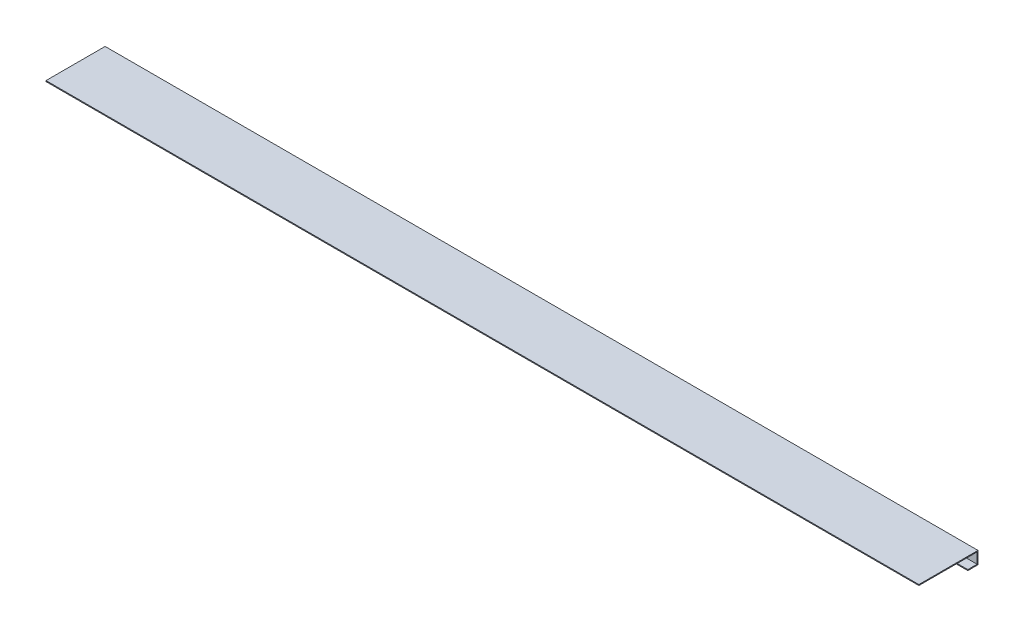
SolidWorks part; units mm, degrees
ref_plane "Front Plane" through (0, 0, 0) normal (0, 0, 1) x (1, 0, 0)
ref_plane "Top Plane" through (0, 0, 0) normal (0, 1, 0) x (1, 0, 0)
ref_plane "Right Plane" through (0, 0, 0) normal (1, 0, 0) x (0, 0, -1)
sketch "Sketch1" plane through (0, 0, 0) normal (1, 0, 0) x (0, 0, -1)
  line L0 (0, 0) -> (128, 0)
  line L1 (128, 0) -> (128, -27)
  line L2 (128, -27) -> (106, -27)
  line L3 (0, -2) -> (126, -2)
  line L4 (126, -2) -> (126, -25)
  line L5 (126, -25) -> (106, -25)
  line L6 (0, 0) -> (0, -2)
  line L7 (106, -27) -> (106, -25)
  dimension "D1" = 2
  dimension "D2" = 128
  dimension "D3" = 27
  dimension "D4" = 22
extrude "Boss-Extrude1" add sketch "Sketch1" along normal blind 1890
equation "\"door_base_long7_R1_L_open_Single_height\"=1890.0"
equation "\"D1@Boss-Extrude1\"= \"door_base_long7_L1_L_open_Single_height\""
equation "\"CarBeamWidth\"=700.0"
equation "\"WheelWidth\"=650.0"
equation "\"Wheel_FrontBoxDistance\"=1390.0"
equation "\"MetalSheet_3mm_length\"=5030.0"
equation "\"MetalSheet_3mm_width\"=1923.0"
equation "\"MetalSheet_3mm_FloorCut_L_length\"=1764.0"
equation "\"MetalSheet_3mm_FloorCut_L_disdance\"=1665.0"
equation "\"MetalSheet_3mm_FloorCut_R_length\"=1764.0"
equation "\"MetalSheet_3mm_FloorCut_R_disdance\"=1665.0"
equation "\"indoorHeight\"=1940.0"
equation "\"haveDoor_R\"=1"
equation "\"side_door_bottom_R_3mm_length\"=1934.0"
equation "\"1Bar_Side_RF_3mm_length\"=1493.0"
equation "\"1Bar_Side_RB_3mm_length\"=1493.0"
equation "\"DoorSeparator_RF_3mm_withHinge_toFrontDistance\"=1673.0"
equation "\"DoorSeparator_RF_3mm_withHinge_exist\"=1"
equation "\"DoorSeparator_RB_3mm_withHinge_toFrontDistance\"=3427.0"
equation "\"DoorSeparator_RB_3mm_withHinge_exist\"=1"
equation "\"Door_R1_L_open_Single_toFrontDistance\"=2547.5"
equation "\"Door_R1_L_open_Single_exist\"=1"
equation "\"door_base_short7_R1_L_open_Single_height\"=1890.0"
equation "\"door_base_short7_R1_L_open_Single_width\"=864"
equation "\"Door_R1_R_open_Single_toFrontDistance\"=3422.0"
equation "\"Door_R1_R_open_Single_exist\"=1"
equation "\"door_base_long7_R1_R_open_Single_height\"=1890.0"
equation "\"door_base_short7_R1_R_open_Single_height\"=1890.0"
equation "\"door_base_short7_R1_R_open_Single_width\"=864"
equation "\"x\"=66.0"
equation "\"da\"=62.0"
equation "\"SquareTube_length\"=1923.0"
equation "\"channelSteel_length\"=5030.0"
equation "\"SquareTube_inFront_AvgDistance\"=285.0"
equation "\"SquareTube_inFront_TotalCount\"=5"
equation "\"SquareTube_inFront1_cutDepth50_R\"=0.5"
equation "\"SquareTube_inFront1_cutDepth50_L\"=0.5"
equation "\"SquareTube_inFront2_cutDepth50_R\"=0.5"
equation "\"SquareTube_inFront2_cutDepth50_L\"=0.5"
equation "\"SquareTube_inFront3_cutDepth50_R\"=0.5"
equation "\"SquareTube_inFront3_cutDepth50_L\"=0.5"
equation "\"SquareTube_inFront4_cutDepth50_R\"=0.5"
equation "\"SquareTube_inFront4_cutDepth50_L\"=0.5"
equation "\"SquareTube_inFront5_cutDepth50_R\"=50"
equation "\"SquareTube_inFront5_cutDepth50_L\"=50"
equation "\"SquareTube_inFront6_cutDepth50_R\"=50"
equation "\"SquareTube_inFront6_cutDepth50_L\"=50"
equation "\"SquareTube_inFront7_cutDepth50_R\"=50"
equation "\"SquareTube_inFront7_cutDepth50_L\"=50"
equation "\"SquareTube_inFront8_cutDepth50_R\"=50"
equation "\"SquareTube_inFront8_cutDepth50_L\"=50"
equation "\"SquareTube_inFront9_cutDepth50_R\"=50"
equation "\"SquareTube_inFront9_cutDepth50_L\"=50"
equation "\"SquareTube_inFront10_cutDepth50_R\"=50"
equation "\"SquareTube_inFront10_cutDepth50_L\"=50"
equation "\"SquareTube_inFront11_cutDepth50_R\"=50"
equation "\"SquareTube_inFront11_cutDepth50_L\"=50"
equation "\"SquareTube_inFront12_cutDepth50_R\"=50"
equation "\"SquareTube_inFront12_cutDepth50_L\"=50"
equation "\"SquareTube_inFront13_cutDepth50_R\"=50"
equation "\"SquareTube_inFront13_cutDepth50_L\"=50"
equation "\"SquareTube_inFront14_cutDepth50_R\"=50"
equation "\"SquareTube_inFront14_cutDepth50_L\"=50"
equation "\"SquareTube_inBack_AvgDistance\"=333.125"
equation "\"SquareTube_inBack_TotalCount\"=9"
equation "\"SquareTube_inBack1_cutDepth50_R\"=50"
equation "\"SquareTube_inBack1_cutDepth50_L\"=50"
equation "\"SquareTube_inBack2_cutDepth50_R\"=50"
equation "\"SquareTube_inBack2_cutDepth50_L\"=50"
equation "\"SquareTube_inBack3_cutDepth50_R\"=50"
equation "\"SquareTube_inBack3_cutDepth50_L\"=50"
equation "\"SquareTube_inBack4_cutDepth50_R\"=50"
equation "\"SquareTube_inBack4_cutDepth50_L\"=50"
equation "\"SquareTube_inBack5_cutDepth50_R\"=50"
equation "\"SquareTube_inBack5_cutDepth50_L\"=50"
equation "\"SquareTube_inBack6_cutDepth50_R\"=0.5"
equation "\"SquareTube_inBack6_cutDepth50_L\"=0.5"
equation "\"SquareTube_inBack7_cutDepth50_R\"=0.5"
equation "\"SquareTube_inBack7_cutDepth50_L\"=0.5"
equation "\"SquareTube_inBack8_cutDepth50_R\"=0.5"
equation "\"SquareTube_inBack8_cutDepth50_L\"=0.5"
equation "\"boxLength\"=5100.0"
equation "\"boxWidth\"=1930.0"
equation "\"indoorHeight_para\"=25.0"
equation "\"rearLightHeight_para\"=265.0"
equation "\"doorColumnBar_A_FR_3mm_length_Cut\"=2310.0"
equation "\"A\"=0.0"
equation "\"side_door_bottom_R_3mm_toFrontDistance\"=1583.0"
equation "\"door_base_double_BL_height\"=1890.0"
equation "\"door_base_short7_BL_Single_height\"=1890.0"
equation "\"door_base_short7_BL_Single_width\"=864"
equation "\"door_base_long7_BR_Single_height\"=1890.0"
equation "\"door_base_short7_BR_Single_height\"=1890.0"
equation "\"door_base_short7_BR_Single_width\"=864"
equation "\"doorColumnBar_A_FL_3mm_length_Cut\"=2310.0"
equation "\"B\"=0.0"
equation "\"haveDoor_L\"=1"
equation "\"side_door_bottom_L_3mm_length\"=1934.0"
equation "\"side_door_bottom_L_3mm_toFrontDistance\"=1583.0"
equation "\"1Bar_Side_LF_3mm_length\"=1493.0"
equation "\"1Bar_Side_LB_3mm_length\"=1493.0"
equation "\"DoorSeparator_LF_3mm_withHinge_toFrontDistance\"=1673.0"
equation "\"DoorSeparator_LF_3mm_withHinge_exist\"=1"
equation "\"DoorSeparator_LB_3mm_withHinge_toFrontDistance\"=3427.0"
equation "\"DoorSeparator_LB_3mm_withHinge_exist\"=1"
equation "\"Door_L1_L_open_Single_toFrontDistance\"=3422.0"
equation "\"Door_L1_L_open_Single_exist\"=1"
equation "\"door_base_long7_L1_L_open_Single_height\"=1890.0"
equation "\"door_base_short7_L1_L_open_Single_height\"=1890.0"
equation "\"door_base_short7_L1_L_open_Single_width\"=864"
equation "\"Door_L1_R_open_Single_toFrontDistance\"=2547.5"
equation "\"Door_L1_R_open_Single_exist\"=1"
equation "\"door_base_long7_L1_R_open_Single_height\"=1890.0"
equation "\"door_base_short7_L1_R_open_Single_height\"=1890.0"
equation "\"door_base_short7_L1_R_open_Single_width\"=864"
